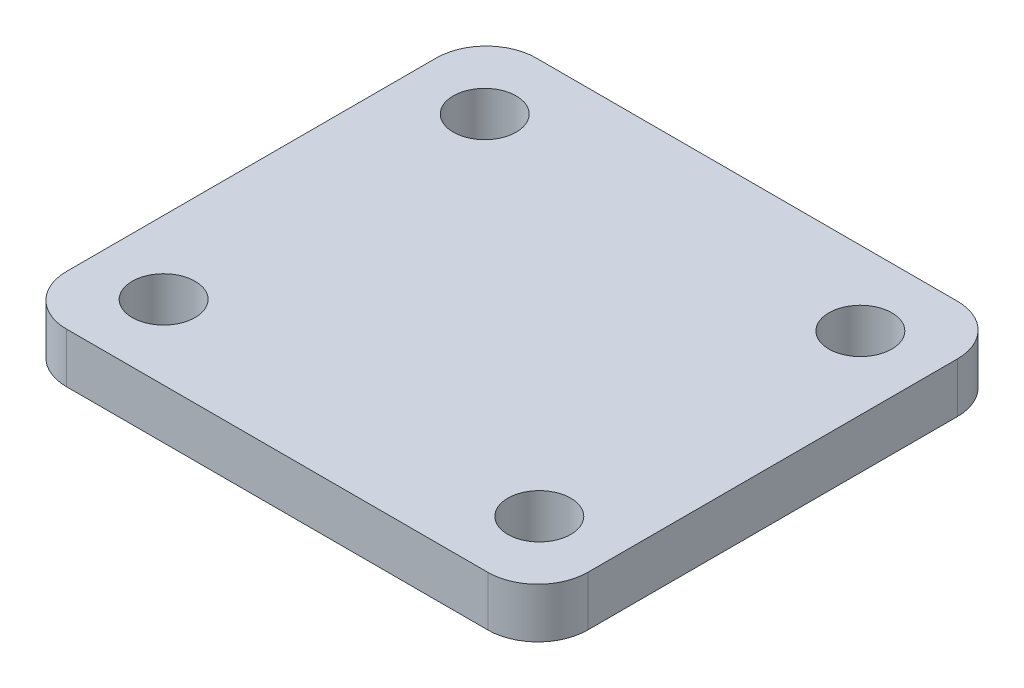
SolidWorks part; units mm, degrees
ref_plane "Front Plane" through (0, 0, 0) normal (0, 0, 1) x (1, 0, 0)
ref_plane "Top Plane" through (0, 0, 0) normal (0, 1, 0) x (1, 0, 0)
ref_plane "Right Plane" through (0, 0, 0) normal (1, 0, 0) x (0, 0, -1)
sketch "Sketch1" plane through (0, 0, 0) normal (0, 1, 0) x (1, 0, 0)
  line L1 (-10.71, -11.9375) -> (10.71, -11.9375)
  line L2 (-13.25, -9.3975) -> (-13.25, 9.3975)
  line L3 (-10.71, 11.9375) -> (10.71, 11.9375)
  line L4 (13.25, -9.3975) -> (13.25, 9.3975)
  arc A0 (10.71, 11.9375) -> (13.25, 9.3975) centre (10.71, 9.3975) cw
  arc A1 (10.71, -11.9375) -> (13.25, -9.3975) centre (10.71, -9.3975) ccw
  arc A2 (-10.71, -11.9375) -> (-13.25, -9.3975) centre (-10.71, -9.3975) cw
  arc A3 (-13.25, 9.3975) -> (-10.71, 11.9375) centre (-10.71, 9.3975) cw
  point P7 (-2.4955, -0.2971)
  point P8 (13.25, 11.9375)
  point P11 (13.25, -11.9375)
  point P14 (-13.25, -11.9375)
  dimension "D5" = 2.54
  dimension "D1" = 26.5
  dimension "D2" = 23.875
  dimension "D3" = 13.25
  dimension "D4" = 11.9375
extrude "Boss-Extrude1" add sketch "Sketch1" along normal blind 2.54
sketch "Sketch2" plane through (0, 2.54, 0) normal (0, 1, 0) x (1, 0, 0)
  circle A0 centre (-9.55, 8.1625) radius 1.6
  circle A1 centre (9.55, 8.1625) radius 1.6
  circle A2 centre (9.55, -8.1625) radius 1.6
  circle A3 centre (-9.55, -8.1625) radius 1.6
  point P8 (7.3424, 4.9969)
  point P9 (0, 0)
  point P10 (9.5859, -4.3035)
  point P11 (0, 0)
  point P12 (-10.9728, -8.5865)
  point P15 (-11.5031, 5.7719)
  point P16 (-33.5303, 12.0538)
  dimension "D1" = 3.2
  dimension "D2" = 3.2
  dimension "D3" = 3.2
  dimension "D4" = 3.2
  dimension "D6" = 0
  dimension "D5" = 19.1
  dimension "D7" = 19.1
  dimension "D8" = 0
  dimension "D9" = 16.325
  dimension "D10" = 0
  dimension "D11" = 9.55
  dimension "D12" = 8.1625
extrude "Cut-Extrude1" cut sketch "Sketch2" against normal through all
